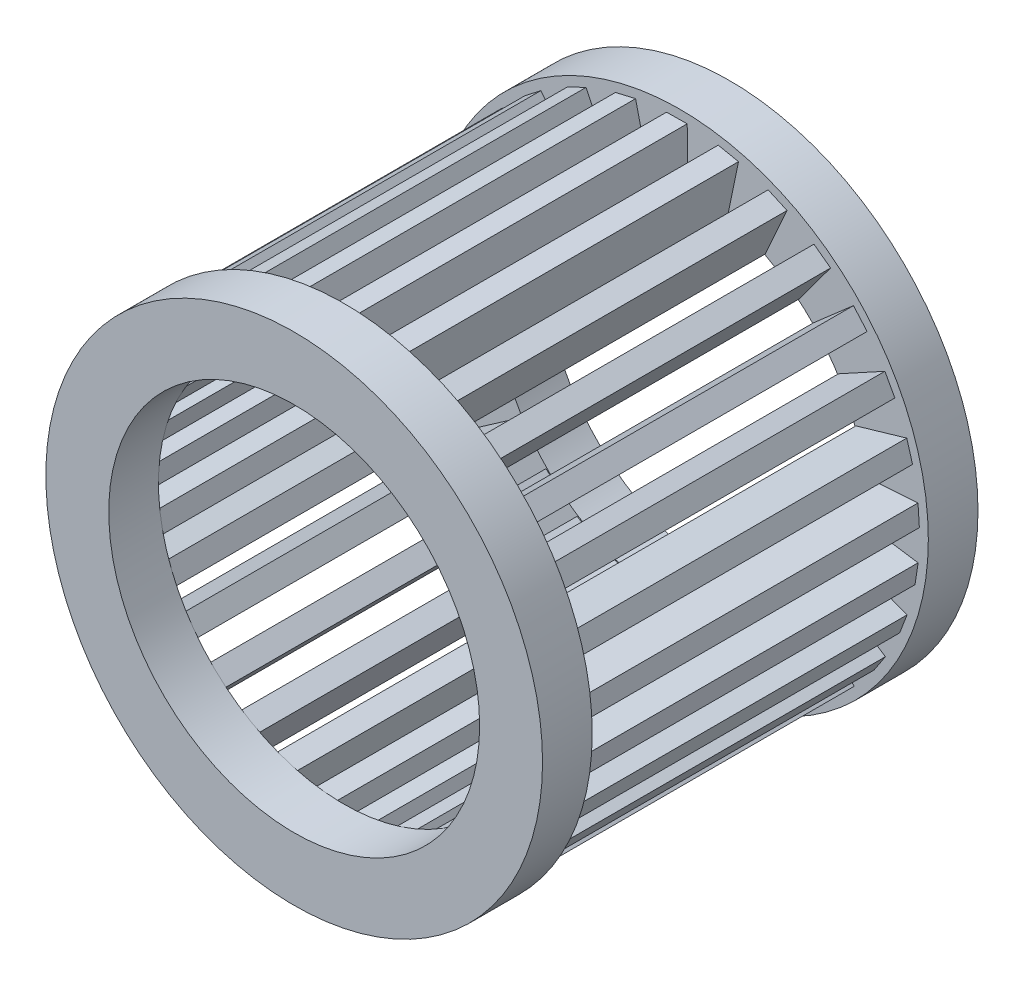
SolidWorks part; units mm, degrees
ref_plane "Спереди" through (0, 0, 0) normal (0, 0, 1) x (1, 0, 0)
ref_plane "Сверху" through (0, 0, 0) normal (0, 1, 0) x (1, 0, 0)
ref_plane "Справа" through (0, 0, 0) normal (1, 0, 0) x (0, 0, -1)
sketch "Эскиз1" plane through (0, 0, 0) normal (0, 0, 1) x (1, 0, 0)
  line L0 (22.5332, 0.2629) -> (28.9187, 0.6924)
  line L1 (28.9187, 0.6924) -> (28.7509, 3.1868)
  line L2 (28.7509, 3.1868) -> (22.3654, 2.7573)
  line L3 (22.3654, 2.7573) -> (22.5332, 0.2629)
  line L4 (21.9498, 5.1007) -> (28.0938, 6.8929)
  line L5 (28.0938, 6.8929) -> (27.3937, 9.2929)
  line L6 (27.3937, 9.2929) -> (21.2498, 7.5007)
  line L7 (21.2498, 7.5007) -> (21.9498, 5.1007)
  line L8 (20.3402, 9.7) -> (25.9552, 12.7711)
  line L9 (25.9552, 12.7711) -> (24.7556, 14.9645)
  line L10 (24.7556, 14.9645) -> (19.1405, 11.8934)
  line L11 (19.1405, 11.8934) -> (20.3402, 9.7)
  line L12 (17.7794, 13.8458) -> (22.603, 18.0521)
  line L13 (22.603, 18.0521) -> (20.9599, 19.9363)
  line L14 (20.9599, 19.9363) -> (16.1363, 15.73)
  line L15 (16.1363, 15.73) -> (17.7794, 13.8458)
  line L16 (14.3873, 17.3441) -> (18.1938, 22.489)
  line L17 (18.1938, 22.489) -> (16.1841, 23.976)
  line L18 (16.1841, 23.976) -> (12.3776, 18.8311)
  line L19 (12.3776, 18.8311) -> (14.3873, 17.3441)
  line L20 (10.3225, 20.0315) -> (12.934, 25.8744)
  line L21 (12.934, 25.8744) -> (10.6516, 26.8945)
  line L22 (10.6516, 26.8945) -> (8.0401, 21.0516)
  line L23 (8.0401, 21.0516) -> (10.3225, 20.0315)
  line L24 (5.7749, 21.7822) -> (7.0694, 28.0499)
  line L25 (7.0694, 28.0499) -> (4.6211, 28.5555)
  line L26 (4.6211, 28.5555) -> (3.3266, 22.2878)
  line L27 (3.3266, 22.2878) -> (5.7749, 21.7822)
  line L28 (0.9574, 22.5143) -> (0.8742, 28.9138)
  line L29 (0.8742, 28.9138) -> (-1.6256, 28.8813)
  line L30 (-1.6256, 28.8813) -> (-1.5424, 22.4818)
  line L31 (-1.5424, 22.4818) -> (0.9574, 22.5143)
  line L32 (-3.9049, 22.1938) -> (-5.3618, 28.4257)
  line L33 (-5.3618, 28.4257) -> (-7.7962, 27.8566)
  line L34 (-7.7962, 27.8566) -> (-6.3393, 21.6247)
  line L35 (-6.3393, 21.6247) -> (-3.9049, 22.1938)
  line L36 (-8.5846, 20.8355) -> (-11.3472, 26.6085)
  line L37 (-11.3472, 26.6085) -> (-13.6023, 25.5294)
  line L38 (-13.6023, 25.5294) -> (-10.8397, 19.7563)
  line L39 (-10.8397, 19.7563) -> (-8.5846, 20.8355)
  line L40 (-12.8629, 18.5029) -> (-16.8019, 23.5471)
  line L41 (-16.8019, 23.5471) -> (-18.7723, 22.0085)
  line L42 (-18.7723, 22.0085) -> (-14.8333, 16.9642)
  line L43 (-14.8333, 16.9642) -> (-12.8629, 18.5029)
  line L44 (-16.5398, 15.3052) -> (-21.4711, 19.3847)
  line L45 (-21.4711, 19.3847) -> (-23.0646, 17.4584)
  line L46 (-23.0646, 17.4584) -> (-18.1333, 13.3789)
  line L47 (-18.1333, 13.3789) -> (-16.5398, 15.3052)
  line L48 (-19.4432, 11.3918) -> (-25.1362, 14.3158)
  line L49 (-25.1362, 14.3158) -> (-26.2784, 12.092)
  line L50 (-26.2784, 12.092) -> (-20.5854, 9.168)
  line L51 (-20.5854, 9.168) -> (-19.4432, 11.3918)
  line L52 (-21.4376, 6.9457) -> (-27.626, 8.5776)
  line L53 (-27.626, 8.5776) -> (-28.2635, 6.1602)
  line L54 (-28.2635, 6.1602) -> (-22.075, 4.5284)
  line L55 (-22.075, 4.5284) -> (-21.4376, 6.9457)
  line L56 (-22.4295, 2.1749) -> (-28.8241, 2.4383)
  line L57 (-28.8241, 2.4383) -> (-28.927, -0.0596)
  line L58 (-28.927, -0.0596) -> (-22.5324, -0.323)
  line L59 (-22.5324, -0.323) -> (-22.4295, 2.1749)
  line L60 (-22.3726, -2.6976) -> (-28.6743, -3.815)
  line L61 (-28.6743, -3.815) -> (-28.2379, -6.2766)
  line L62 (-28.2379, -6.2766) -> (-21.9362, -5.1592)
  line L63 (-21.9362, -5.1592) -> (-22.3726, -2.6976)
  line L64 (-21.2697, -7.444) -> (-27.1838, -9.89)
  line L65 (-27.1838, -9.89) -> (-26.2284, -12.2002)
  line L66 (-26.2284, -12.2002) -> (-20.3142, -9.7542)
  line L67 (-20.3142, -9.7542) -> (-21.2697, -7.444)
  line L68 (-19.1722, -11.8423) -> (-24.4222, -15.5025)
  line L69 (-24.4222, -15.5025) -> (-22.9925, -17.5533)
  line L70 (-22.9925, -17.5533) -> (-17.7424, -13.8931)
  line L71 (-17.7424, -13.8931) -> (-19.1722, -11.8423)
  line L72 (-16.1782, -15.6869) -> (-20.5187, -20.3901)
  line L73 (-20.5187, -20.3901) -> (-18.6815, -22.0856)
  line L74 (-18.6815, -22.0856) -> (-14.341, -17.3824)
  line L75 (-14.341, -17.3824) -> (-16.1782, -15.6869)
  line L76 (-12.4277, -18.798) -> (-15.6557, -24.3243)
  line L77 (-15.6557, -24.3243) -> (-13.497, -25.5852)
  line L78 (-13.497, -25.5852) -> (-10.269, -20.0589)
  line L79 (-10.269, -20.0589) -> (-12.4277, -18.798)
  line L80 (-8.0962, -21.0301) -> (-10.0607, -27.1211)
  line L81 (-10.0607, -27.1211) -> (-7.6814, -27.8885)
  line L82 (-7.6814, -27.8885) -> (-5.7168, -21.7975)
  line L83 (-5.7168, -21.7975) -> (-8.0962, -21.0301)
  line L84 (-3.386, -22.2789) -> (-3.9952, -28.6498)
  line L85 (-3.9952, -28.6498) -> (-1.5066, -28.8878)
  line L86 (-1.5066, -28.8878) -> (-0.8974, -22.5168)
  line L87 (-0.8974, -22.5168) -> (-3.386, -22.2789)
  line L88 (1.4824, -22.4859) -> (2.257, -28.8388)
  line L89 (2.257, -28.8388) -> (4.7387, -28.5362)
  line L90 (4.7387, -28.5362) -> (3.9641, -22.1833)
  line L91 (3.9641, -22.1833) -> (1.4824, -22.4859)
  line L92 (6.2816, -21.6415) -> (8.4038, -27.6794)
  line L93 (8.4038, -27.6794) -> (10.7623, -26.8504)
  line L94 (10.7623, -26.8504) -> (8.6401, -20.8125)
  line L95 (8.6401, -20.8125) -> (6.2816, -21.6415)
  line L96 (10.787, -19.7852) -> (14.1575, -25.2257)
  line L97 (14.1575, -25.2257) -> (16.2828, -23.9091)
  line L98 (16.2828, -23.9091) -> (12.9122, -18.4686)
  line L99 (12.9122, -18.4686) -> (10.787, -19.7852)
  line L100 (14.788, -17.0037) -> (19.2493, -21.5925)
  line L101 (19.2493, -21.5925) -> (21.0418, -19.8498)
  line L102 (21.0418, -19.8498) -> (16.5805, -15.261)
  line L103 (16.5805, -15.261) -> (14.788, -17.0037)
  line L104 (18.0976, -13.4272) -> (23.441, -16.9496)
  line L105 (23.441, -16.9496) -> (24.817, -14.8623)
  line L106 (24.817, -14.8623) -> (19.4735, -11.3399)
  line L107 (19.4735, -11.3399) -> (18.0976, -13.4272)
  line L108 (20.5609, -9.2228) -> (26.5367, -11.5142)
  line L109 (26.5367, -11.5142) -> (27.4318, -9.18)
  line L110 (27.4318, -9.18) -> (21.456, -6.8886)
  line L111 (21.456, -6.8886) -> (20.5609, -9.2228)
  line L112 (22.0629, -4.5872) -> (28.3915, -5.5404)
  line L113 (28.3915, -5.5404) -> (28.7638, -3.0683)
  line L114 (28.7638, -3.0683) -> (22.4352, -2.1151)
  line L115 (22.4352, -2.1151) -> (22.0629, -4.5872)
extrude "Bars" add sketch "Эскиз1" along normal blind 40.8 from offset 20.4 separate body
sketch "Эскиз2" plane through (0, 0, 0) normal (0, 0, 1) x (1, 0, 0)
  circle A0 centre (0, 0) radius 30
  circle A1 centre (0, 0) radius 22.4
extrude "End_ring_front" add sketch "Эскиз2" along normal blind 6 from offset 20.3
sketch "Эскиз3" plane through (0, 0, 0) normal (0, 0, 1) x (1, 0, 0)
  circle A0 centre (0, 0) radius 30
  circle A1 centre (0, 0) radius 22.4
extrude "End_ring_rear" add sketch "Эскиз3" along normal blind 6 from offset 26.3
